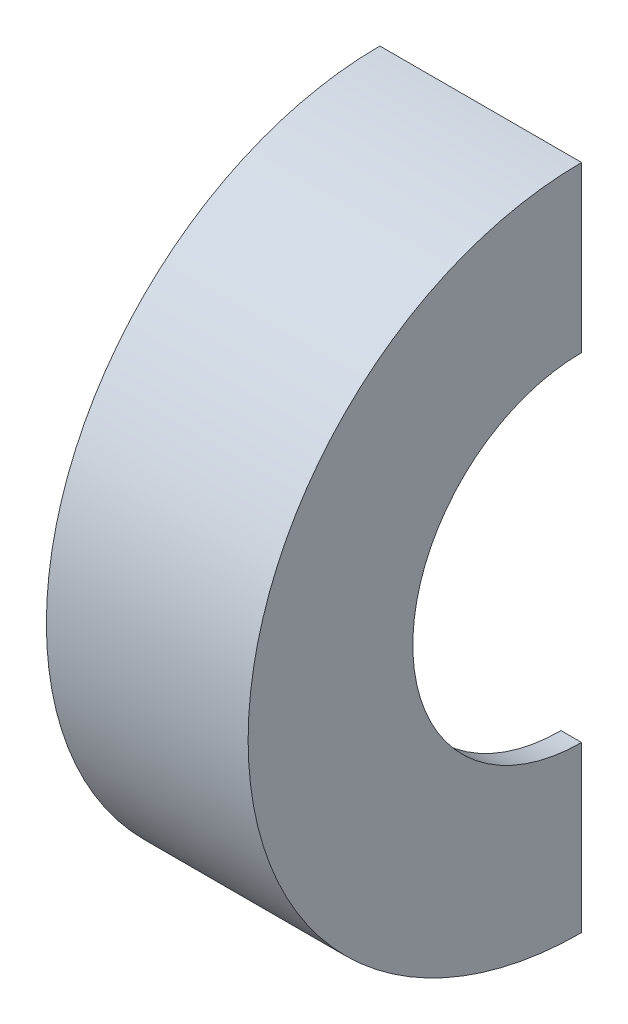
SolidWorks part; units mm, degrees
ref_plane "前视基准面" through (0, 0, 0) normal (0, 0, 1) x (1, 0, 0)
ref_plane "上视基准面" through (0, 0, 0) normal (0, 1, 0) x (1, 0, 0)
ref_plane "右视基准面" through (0, 0, 0) normal (1, 0, 0) x (0, 0, -1)
sketch "草图1" plane through (0, 0, 0) normal (0, 0, 1) x (1, 0, 0)
  line L1 (0, 0) -> (98, 0) construction
  line L2 (0, 82) -> (0, 162)
  line L3 (0, 162) -> (98, 162)
  line L4 (98, 82) -> (98, 162)
  line L5 (0, 82) -> (10, 82)
  line L8 (10, 82) -> (10, 152)
  line L9 (10, 152) -> (88, 152)
  line L10 (88, 152) -> (88, 82)
  line L11 (88, 82) -> (98, 82)
  point P2 (10, 151.1698)
  point P10 (88, 151.1698)
  point P11 (98, 161.2632)
  point P15 (0, 0)
  point P16 (0, 161.0257)
revolve "旋转1" add sketch "草图1" angle 180 about L1
